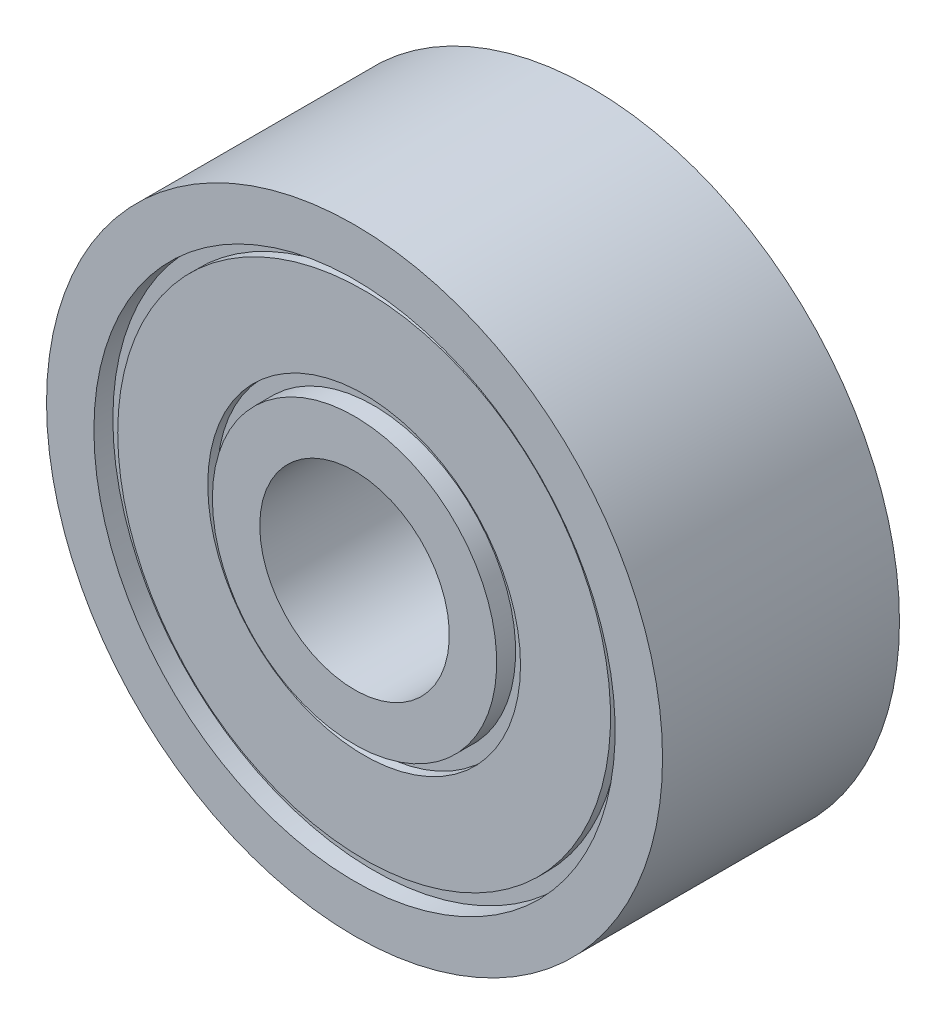
SolidWorks part; units mm, degrees
ref_plane "Front Plane" through (0, 0, 0) normal (0, 0, 1) x (1, 0, 0)
ref_plane "Top Plane" through (0, 0, 0) normal (0, 1, 0) x (1, 0, 0)
ref_plane "Right Plane" through (0, 0, 0) normal (1, 0, 0) x (0, 0, -1)
ref_plane "Plane1" through (0, 0, 7) normal (0, 0, 1) x (1, 0, 0)
sketch "Sketch1" plane through (0, 0, 7) normal (0, 0, 1) x (1, 0, 0)
  circle A0 centre (0, 0) radius 2
  circle A1 centre (0, 0) radius 6.5
  dimension "D1" = 13
  dimension "D2" = 4
extrude "Boss-Extrude1" add sketch "Sketch1" against normal blind 5
sketch "Sketch4" plane through (0, 0, 0) normal (0, 1, 0) x (1, 0, 0)
  line L2 (3, -2.4) -> (3, -2)
  line L3 (3.3, -2.4) -> (3, -2.4)
  line L9 (0, -2) -> (0, -7) construction
  line L10 (3.3, -2.2027) -> (3.3, -2.4)
  line L11 (5.2, -2.2027) -> (3.3, -2.2027)
  line L12 (5.2, -2.4) -> (5.2, -2.2027)
  line L13 (5.5, -2.4) -> (5.2, -2.4)
  line L14 (5.5, -2) -> (5.5, -2.4)
  line L15 (2, -2) -> (-2, -2) construction
  line L17 (5.5, -7) -> (3, -7)
  line L19 (-55, -7) -> (55, -7) construction
  line L20 (0, -4.5) -> (6.5, -4.5) construction
  line L21 (6.5, -7) -> (6.5, -2) construction
  line L22 (6.5, -2) -> (-6.5, -2) construction
  line L23 (5.5, -2) -> (3, -2)
  line L24 (5.5, -7) -> (5.5, -6.6)
  line L25 (5.5, -6.6) -> (5.2, -6.6)
  line L26 (5.2, -6.6) -> (5.2, -6.7974)
  line L27 (5.2, -6.7974) -> (3.3, -6.7974)
  line L28 (3.3, -6.7974) -> (3.3, -6.6)
  line L29 (3.3, -6.6) -> (3, -6.6)
  line L30 (3, -6.6) -> (3, -7)
  point P22 (0, 0)
  point P23 (0, 0)
  point P25 (3.3541, -2.2027)
  dimension "D1" = 1
  dimension "D2" = 1
  dimension "D3" = 0.4
  dimension "D4" = 0.3
revolve "Cut-Revolve1" cut sketch "Sketch4" angle 360 about L9
